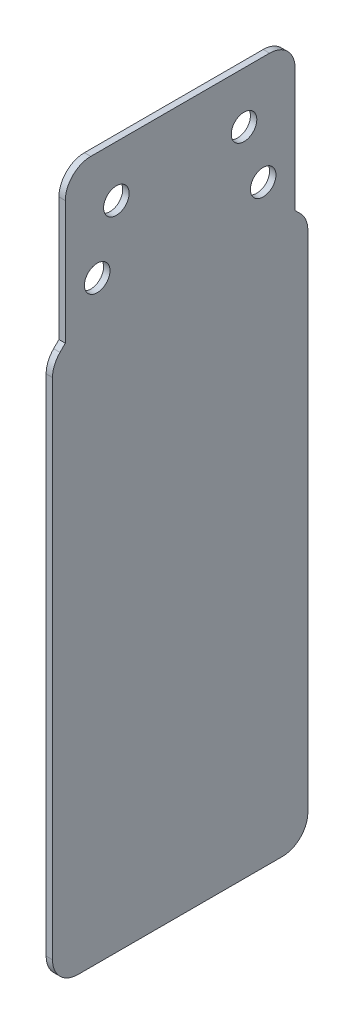
SolidWorks part; units mm, degrees
material "PVC 0.007 Plasticized"
ref_plane "Front Plane" through (0, 0, 0) normal (0, 0, 1) x (1, 0, 0)
ref_plane "Top Plane" through (0, 0, 0) normal (0, 1, 0) x (1, 0, 0)
ref_plane "Right Plane" through (0, 0, 0) normal (1, 0, 0) x (0, 0, -1)
sketch "Sketch1" plane through (0, 0, 0) normal (1, 0, 0) x (0, 0, -1)
  line L1 (-18, 0) -> (18, 0)
  line L2 (-18, 0) -> (-18, -110)
  line L3 (-18, -110) -> (18, -110)
  line L4 (18, 0) -> (18, -110)
  line L5 (-18, 0) -> (18, -110) construction
  line L6 (-18, -110) -> (18, 0) construction
  point P4 (0, -55)
  point P5 (0, 0)
  dimension "D1" = 110
  dimension "D2" = 36
extrude "Boss-Extrude1" add sketch "Sketch1" along normal blind 1 contours L2 L3 L4 L1
hole_wizard "Ø4.0 (4) Diameter Hole2" positions "Sketch2" profile "Sketch3" hole size "Ø4.0" standard "ISO" end condition through all
sketch "Sketch2" plane through (0, 0, 0) normal (-1, 0, 0) x (0, 0, 1)
  line L0 (18, 0) -> (-18, 0) construction
  line L1 (18, 0) -> (18, -110) construction
  line L2 (-18, 0) -> (-18, -110) construction
  point P0 (-10, -8)
  point P3 (10, -8)
  dimension "D1" = 8
  dimension "D2" = 8
  dimension "D3" = 8
  dimension "D4" = 8
sketch "Sketch3" plane through (0, -8, -10) normal (0, 1, 0) x (0, 0, 1)
  line L0 (0, 0) -> (0, 1)
  line L1 (0, 1) -> (2, 1)
  line L2 (2, 1) -> (2, 0)
  line L5 (2, 0) -> (0, 0)
  line L11 (0, -6.35) -> (0, 107.95) construction
  dimension "Thru Hole Dia." = 4
  dimension "Thru Hole Depth" = 1
hole_wizard "Ø4.0 (4) Diameter Hole3" positions "Sketch4" profile "Sketch5" hole size "Ø4.0" standard "ISO" end condition through all
sketch "Sketch4" plane through (0, 0, 0) normal (-1, 0, 0) x (0, 0, 1)
  line L0 (-18, 0) -> (-18, -110) construction
  line L1 (18, 0) -> (18, -110) construction
  line L2 (18, 0) -> (-18, 0) construction
  point P0 (-13, -17)
  point P3 (13, -17)
  dimension "D1" = 5
  dimension "D2" = 5
  dimension "D3" = 17
  dimension "D4" = 17
sketch "Sketch5" plane through (0, -17, -13) normal (0, 1, 0) x (0, 0, 1)
  line L0 (0, 0) -> (0, 1)
  line L1 (0, 1) -> (2, 1)
  line L2 (2, 1) -> (2, 0)
  line L5 (2, 0) -> (0, 0)
  line L11 (0, -6.35) -> (0, 107.95) construction
  dimension "Thru Hole Dia." = 4
  dimension "Thru Hole Depth" = 1
sketch "Sketch6" plane through (1, 0, 0) normal (1, 0, 0) x (0, 0, -1)
  line L0 (-18, -110) -> (18, -110) construction
  point P0 (-6, -94)
  point P1 (6, -94)
  dimension "D1" = 12
  dimension "D2" = 6
  dimension "D3" = 16
sketch "Sketch9" plane through (0, 0, 0) normal (-1, 0, 0) x (0, 0, 1)
  line L0 (18, -23.35) -> (20, -25.35)
  line L1 (18, 0) -> (18, -110) construction
  line L2 (20, -25.35) -> (20, -110)
  line L4 (18, -110) -> (18, -23.35)
  line L5 (-18, -23.35) -> (-20, -25.35)
  line L6 (-18, 0) -> (-18, -110) construction
  line L7 (-20, -25.35) -> (-20, -110)
  line L9 (-18, -110) -> (-18, -23.35)
  line L10 (-18, -110) -> (-20, -110)
  line L11 (18, -110) -> (20, -110)
  circle A0 centre (13, -17) radius 2 construction
  circle A2 centre (-13, -17) radius 2 construction
  dimension "D2" = 6.35
  dimension "D5" = 6.35
  dimension "D1" = 2
  dimension "D3" = 45
  dimension "D4" = 2
  dimension "D6" = 45
extrude "Boss-Extrude2" add sketch "Sketch9" against normal up to surface (1 mm away) up to face at (1, -17, -11)
fillet "Fillet1" radius 4 2 edges at (0.5, 0, 18) (0.5, 0, -18)
fillet "Fillet2" radius 4 4 edges at (0.5, -25.35, 20) (0.5, -25.35, -20) (0.5, -110, -20) (0.5, -110, 20)
